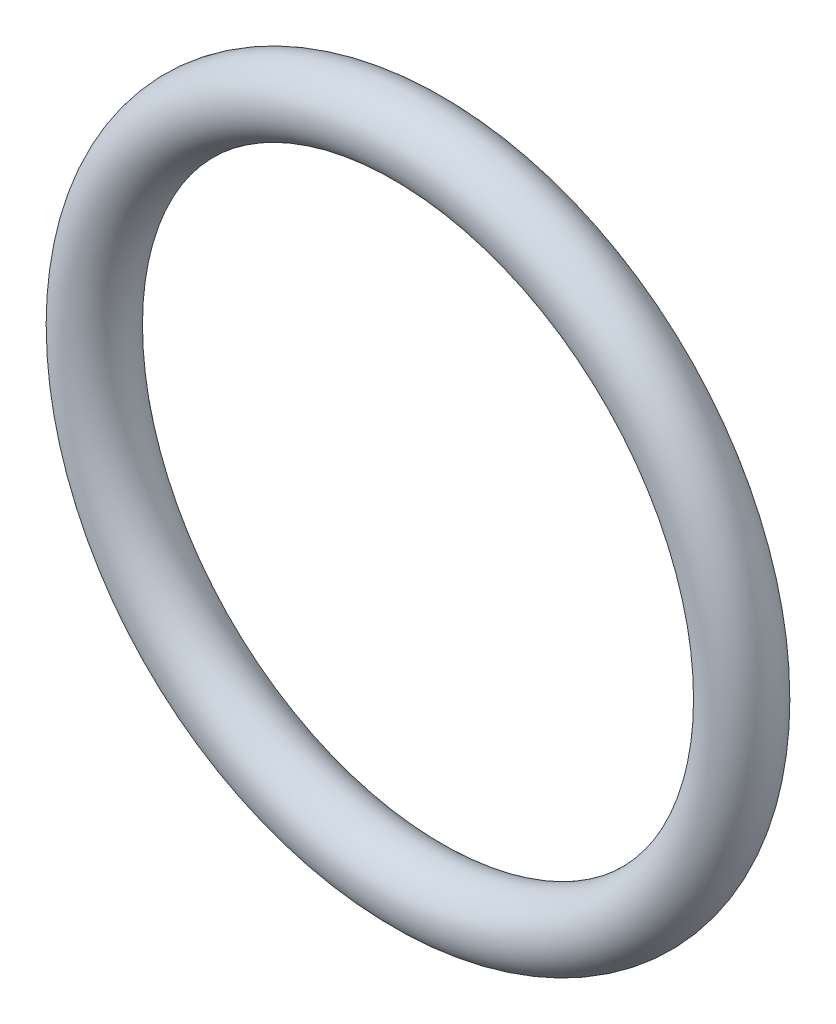
SolidWorks part; units mm, degrees
ref_plane "Front" through (0, 0, 0) normal (0, 0, 1) x (1, 0, 0)
ref_plane "Top" through (0, 0, 0) normal (0, 1, 0) x (1, 0, 0)
ref_plane "Right" through (0, 0, 0) normal (1, 0, 0) x (0, 0, -1)
sketch "Sketch1" plane through (0, 0, 0) normal (1, 0, 0) x (0, -1, 0)
  line L0 (0, -1) -> (0, 1) construction
  line L2 (-11.55, 0) -> (11.55, 0) construction
  line L3 (-8.5, 0) -> (8.5, 0) construction
  circle A0 centre (9.5, 0) radius 1
  point P9 (8.5, 0)
  point P10 (10.5, 0)
  point P13 (9.5, 1)
  point P14 (9.5, -1)
  dimension "Width" = 2
  dimension "ID" = 17
revolve "Revolve1" add sketch "Sketch1" angle 360 about L0
